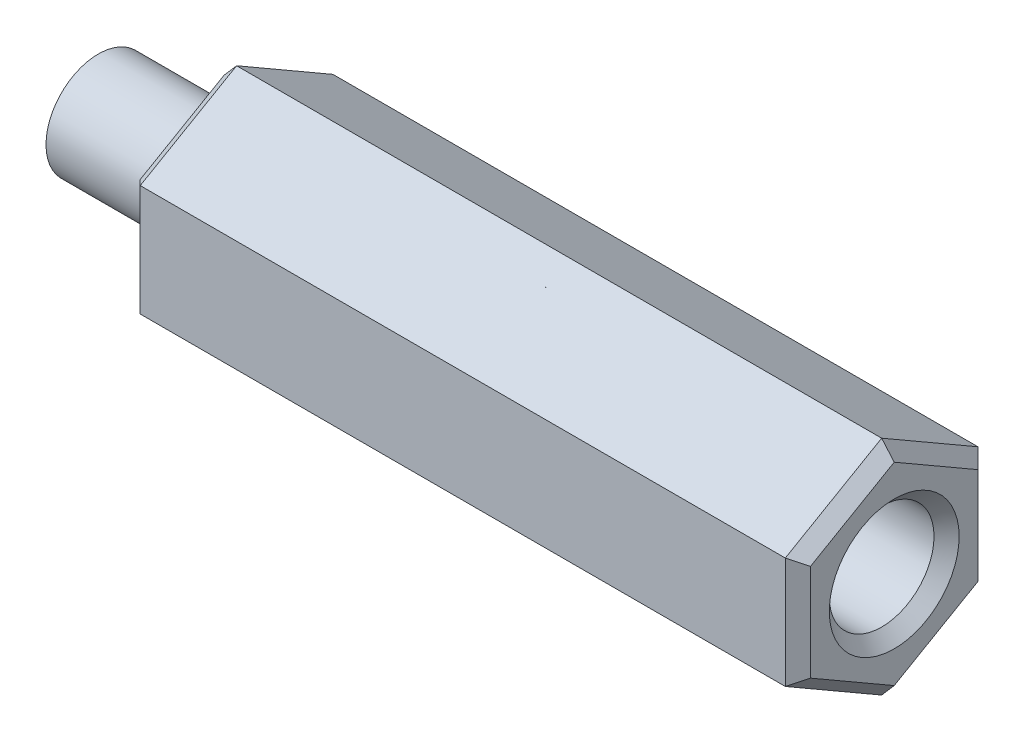
SolidWorks part; units mm, degrees
material "黄铜"
ref_plane "前视基准面" through (0, 0, 0) normal (1, 0, 0) x (0, 1, 0)
ref_plane "上视基准面" through (0, 0, 0) normal (0, 0, 1) x (0, 1, 0)
ref_plane "右视基准面" through (0, 0, 0) normal (0, 1, 0) x (-1, 0, 0)
other "Configuration Table"
sketch "草图1" plane through (0, 0, 0) normal (1, 0, 0) x (0, 1, 0)
  line L0 (0, 0) -> (2.6558, 0) construction
  line L1 (2.6558, 0) -> (1.3279, 2.3)
  line L2 (1.3279, 2.3) -> (-1.3279, 2.3)
  line L3 (-1.3279, 2.3) -> (-2.6558, 0)
  line L4 (-2.6558, 0) -> (-1.3279, -2.3)
  line L5 (-1.3279, -2.3) -> (1.3279, -2.3)
  line L6 (1.3279, -2.3) -> (2.6558, 0)
  circle A0 centre (0, 0) radius 1.25
  circle A1 centre (0, 0) radius 2.3 construction
  dimension "D1" = 2.5
  dimension "D2" = 4.6
extrude "凸台-拉伸1" add sketch "草图1" along normal blind 16
chamfer "倒角1" distance 0.3 angle 45 14 edges at (0, 0, -1.25) (0, 1.9919, 1.15) (0, 0, 2.3) (0, -1.9919, 1.15) (0, -1.9919, -1.15) (0, 0, -2.3) (0, 1.9919, -1.15) (16, 0, -1.25) (16, 0, -2.3) (16, -1.9919, -1.15) (16, -1.9919, 1.15) (16, 0, 2.3) (16, 1.9919, 1.15) (16, 1.9919, -1.15)
sketch "草图2" plane through (0, 0, 0) normal (-1, 0, 0) x (0, 0, 1)
  circle A0 centre (0, 0) radius 1.55
extrude "凸台-拉伸2" add sketch "草图2" against normal blind 2
sketch "草图3" plane through (0, 0, 0) normal (-1, 0, 0) x (0, 0, 1)
  circle A0 centre (0, 0) radius 1.25
  dimension "D1" = 2.5
extrude "凸台-拉伸3" add sketch "草图3" along normal blind 3
cosmetic thread "装饰螺纹线1" parameters "D1"=5, "D2"=1.5
